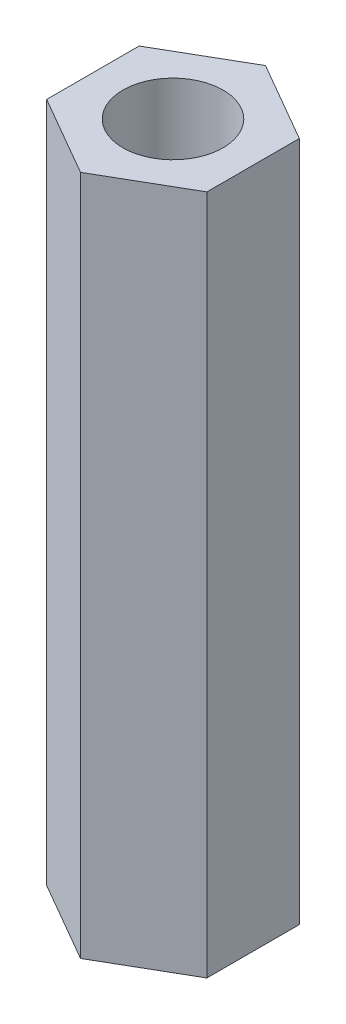
SolidWorks part; units mm, degrees
ref_plane "前视基准面" through (0, 0, 0) normal (0, 0, 1) x (1, 0, 0)
ref_plane "上视基准面" through (0, 0, 0) normal (0, 1, 0) x (1, 0, 0)
ref_plane "右视基准面" through (0, 0, 0) normal (1, 0, 0) x (0, 0, -1)
sketch "草图1" plane through (0, 0, 0) normal (0, 1, 0) x (1, 0, 0)
  line L1 (0, 4.6188) -> (-4, 2.3094)
  line L2 (-4, 2.3094) -> (-4, -2.3094)
  line L3 (-4, -2.3094) -> (0, -4.6188)
  line L4 (0, -4.6188) -> (4, -2.3094)
  line L5 (4, -2.3094) -> (4, 2.3094)
  line L6 (4, 2.3094) -> (0, 4.6188)
  circle A0 centre (0, 0) radius 4 construction
  circle A1 centre (0, 0) radius 2.5
  dimension "D1" = 5
  dimension "D2" = 8
extrude "凸台-拉伸1" add sketch "草图1" along normal blind 34
